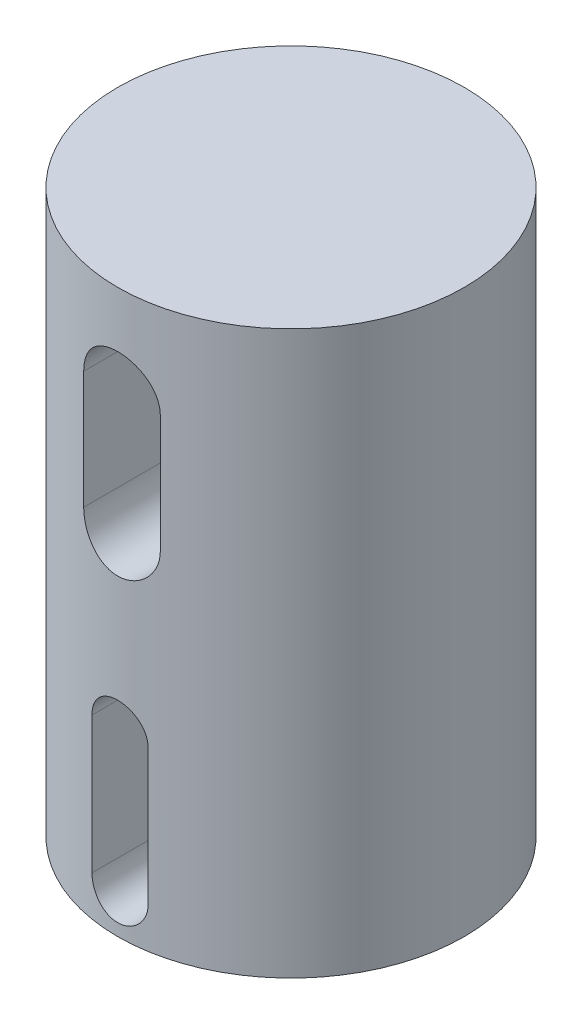
SolidWorks part; units mm, degrees
ref_plane "前视基准面" through (0, 0, 0) normal (0, 0, 1) x (1, 0, 0)
ref_plane "上视基准面" through (0, 0, 0) normal (0, 1, 0) x (1, 0, 0)
ref_plane "右视基准面" through (0, 0, 0) normal (1, 0, 0) x (0, 0, -1)
other "Configuration Table"
sketch "草图1" plane through (0, 0, 0) normal (0, 1, 0) x (1, 0, 0)
  circle A0 centre (0, 0) radius 40.0612
extrude "凸台-拉伸1" add sketch "草图1" along normal blind 130
ref_plane "基准面1" through (0, 0, 40.0612) normal (0, 0, 1) x (1, 0, 0)
sketch "草图2" plane through (0, 0, 40.0612) normal (0, 0, 1) x (1, 0, 0)
  line L0 (0, 108.2952) -> (0, 81.0622) construction
  line L1 (8.8573, 108.2952) -> (8.8573, 81.0622)
  line L2 (-8.8573, 108.2952) -> (-8.8573, 81.0622)
  line L3 (0, 40.8737) -> (0, 9.2781) construction
  line L4 (6.4778, 40.8737) -> (6.4778, 9.2781)
  line L5 (-6.4778, 40.8737) -> (-6.4778, 9.2781)
  arc A0 (8.8573, 108.2952) -> (-8.8573, 108.2952) centre (0, 108.2952) ccw
  arc A1 (-8.8573, 81.0622) -> (8.8573, 81.0622) centre (0, 81.0622) ccw
  arc A2 (6.4778, 40.8737) -> (-6.4778, 40.8737) centre (0, 40.8737) ccw
  arc A3 (-6.4778, 9.2781) -> (6.4778, 9.2781) centre (0, 9.2781) ccw
  point P3 (0, 94.6787)
  point P8 (0, 25.0759)
extrude "切除-拉伸1" cut sketch "草图2" against normal blind 20
